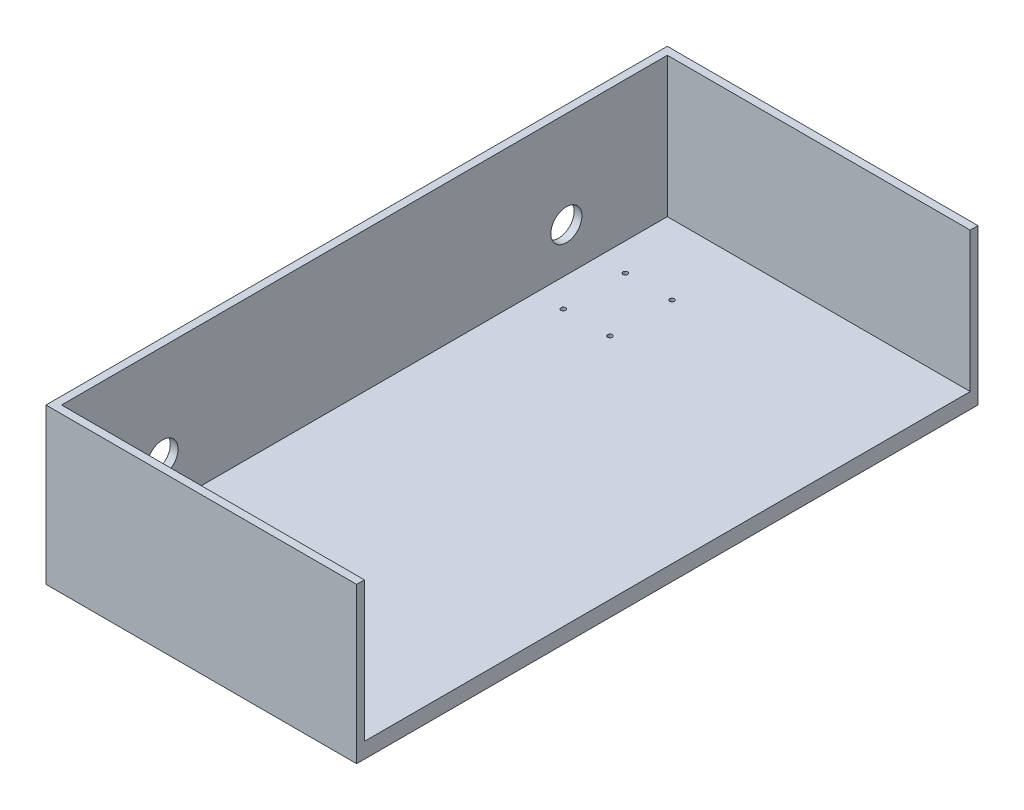
SolidWorks part; units mm, degrees
material "Teck"
ref_plane "Plan de face" through (0, 0, 0) normal (0, 0, 1) x (1, 0, 0)
ref_plane "Plan de dessus" through (0, 0, 0) normal (0, 1, 0) x (1, 0, 0)
ref_plane "Plan de droite" through (0, 0, 0) normal (1, 0, 0) x (0, 0, -1)
sketch "Esquisse1" plane through (0, 0, 0) normal (0, 1, 0) x (1, 0, 0)
  line L1 (0, 0) -> (200, 0)
  line L2 (0, 0) -> (0, 400)
  line L3 (0, 400) -> (200, 400)
  line L4 (200, 0) -> (200, 400)
  dimension "D1" = 400
  dimension "D2" = 200
extrude "Boss.-Extru.1" add sketch "Esquisse1" along normal blind 10
sketch "Esquisse2" plane through (0, 10, 0) normal (0, 1, 0) x (1, 0, 0)
  line L0 (5, 5) -> (5, 395)
  line L2 (0, 0) -> (200, 0) construction
  line L3 (5, 395) -> (200, 395)
  line L4 (200, 0) -> (200, 400) construction
  line L5 (5, 5) -> (200, 5)
  line L6 (200, 5) -> (200, 0)
  line L7 (200, 0) -> (0, 0)
  line L8 (0, 0) -> (0, 400)
  line L9 (0, 400) -> (200, 400)
  line L10 (200, 400) -> (200, 395)
  dimension "D2" = 5
  dimension "D3" = 5
extrude "Boss.-Extru.2" add sketch "Esquisse2" along normal blind 90
sketch "Esquisse3" plane through (5, 0, 0) normal (1, 0, 0) x (0, 0, -1)
  line L0 (395, 100) -> (395, 10) construction
  line L1 (5, 10) -> (395, 10) construction
  circle A0 centre (70, 38) radius 10
  circle A1 centre (330, 38) radius 10
  dimension "D5" = 20
  dimension "D6" = 20
  dimension "D1" = 260
  dimension "D2" = 0
  dimension "D3" = 65
  dimension "D4" = 28
extrude "Enlèv. mat.-Extru.1" cut sketch "Esquisse3" against normal up to next
sketch "Esquisse4" plane through (0, 10, 0) normal (0, 1, 0) x (1, 0, 0)
  line L0 (8, 330) -> (23, 330) construction
  line L1 (5, 395) -> (200, 395) construction
  line L2 (5, 5) -> (5, 395) construction
  line L3 (23, 330) -> (53, 330) construction
  line L4 (23, 310) -> (23, 350) construction
  line L5 (53, 310) -> (53, 350) construction
  line L6 (200, 200) -> (0, 200) construction
  line L7 (200, 5) -> (200, 395) construction
  line L8 (0, 400) -> (0, 0) construction
  line L9 (53, 90) -> (53, 50) construction
  line L10 (23, 90) -> (23, 50) construction
  line L11 (23, 70) -> (53, 70) construction
  line L12 (8, 70) -> (23, 70) construction
  circle A0 centre (23, 350) radius 1.5
  circle A1 centre (53, 350) radius 1.5
  circle A2 centre (53, 310) radius 1.5
  circle A3 centre (23, 310) radius 1.5
  circle A4 centre (23, 90) radius 1.5
  circle A5 centre (53, 90) radius 1.5
  circle A6 centre (53, 50) radius 1.5
  circle A7 centre (23, 50) radius 1.5
  point P10 (23, 330)
  point P12 (53, 330)
  dimension "D7" = 3
  dimension "D8" = 3
  dimension "D9" = 3
  dimension "D10" = 3
  dimension "D1" = 65
  dimension "D2" = 3
  dimension "D3" = 15
  dimension "D4" = 30
  dimension "D5" = 40
  dimension "D6" = 40
extrude "Enlèv. mat.-Extru.2" cut sketch "Esquisse4" against normal blind 5
